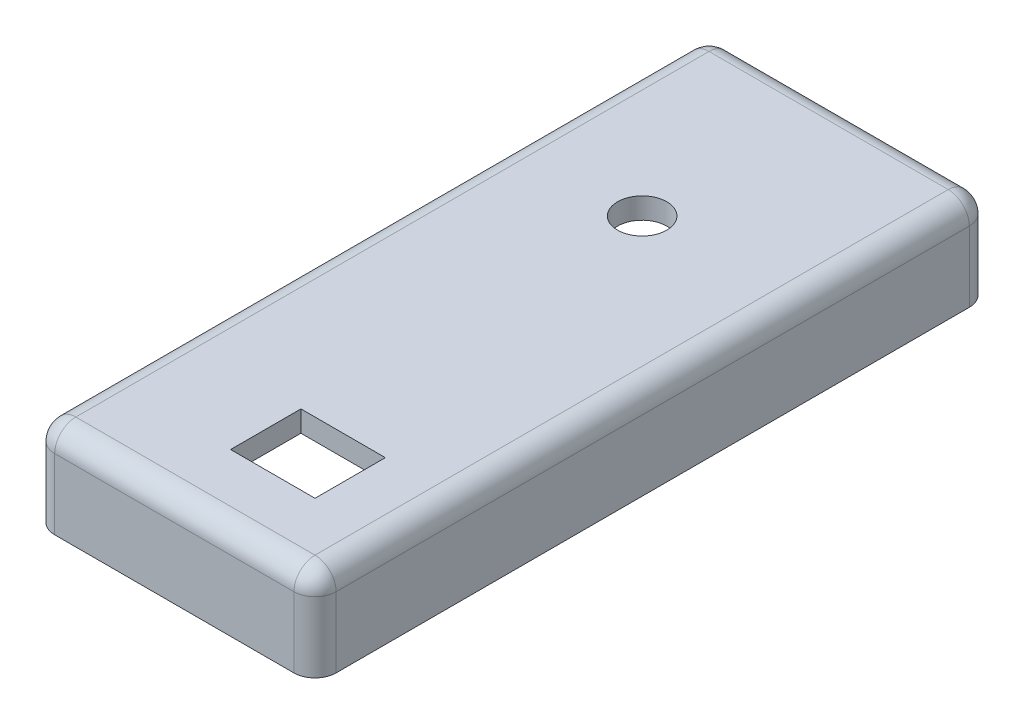
SolidWorks part; units mm, degrees
ref_plane "Plano frontal" through (0, 0, 0) normal (0, 0, 1) x (1, 0, 0)
ref_plane "Plano superior" through (0, 0, 0) normal (0, 1, 0) x (1, 0, 0)
ref_plane "Plano direito" through (0, 0, 0) normal (1, 0, 0) x (0, 0, -1)
sketch "Esboço1" plane through (0, 0, 0) normal (0, 1, 0) x (1, 0, 0)
  line L1 (-18.5576, 45.0701) -> (15.9424, 45.0701)
  line L2 (-18.5576, 45.0701) -> (-18.5576, -45.4299)
  line L3 (-18.5576, -45.4299) -> (15.9424, -45.4299)
  line L4 (15.9424, 45.0701) -> (15.9424, -45.4299)
  line L5 (-21.5576, 48.0701) -> (18.4424, 48.0701)
  line L6 (-21.5576, 48.0701) -> (-21.5576, -47.9299)
  line L7 (-21.5576, -47.9299) -> (18.4424, -47.9299)
  line L8 (18.4424, 48.0701) -> (18.4424, -47.9299)
extrude "Ressalto-extrusão1" add sketch "Esboço1" along normal blind 10
sketch "Esboço2" plane through (0, 10, 0) normal (0, 1, 0) x (1, 0, 0)
  line L1 (-21.5576, -47.9299) -> (18.4424, -47.9299)
  line L2 (-21.5576, -47.9299) -> (-21.5576, 48.0701)
  line L3 (-21.5576, 48.0701) -> (18.4424, 48.0701)
  line L4 (18.4424, -47.9299) -> (18.4424, 48.0701)
extrude "Ressalto-extrusão2" add sketch "Esboço2" along normal blind 3
sketch "Esboço3" plane through (0, 10, 0) normal (0, -1, 0) x (1, 0, 0)
  circle A0 centre (-4.5576, 23.4299) radius 3.5
extrude "Corte-extrusão1" cut sketch "Esboço3" against normal blind 3
sketch "Esboço4" plane through (0, 10, 0) normal (0, -1, 0) x (1, 0, 0)
  line L4 (-13.5576, -41.0701) -> (-1.5576, -41.0701)
  line L5 (-13.5576, -41.0701) -> (-13.5576, -31.0701)
  line L6 (-13.5576, -31.0701) -> (-1.5576, -31.0701)
  line L7 (-1.5576, -41.0701) -> (-1.5576, -31.0701)
extrude "Corte-extrusão2" cut sketch "Esboço4" against normal blind 3
fillet "Filete1" radius 3 8 edges at (-21.5576, 6.5, -48.0701) (18.4424, 6.5, -48.0701) (18.4424, 6.5, 47.9299) (-21.5576, 6.5, 47.9299) (-1.5576, 13, 47.9299) (18.4424, 13, -0.0701) (-1.5576, 13, -48.0701) (-21.5576, 13, -0.0701)
sketch "Esboço5" plane through (0, 10, 0) normal (0, -1, 0) x (1, 0, 0)
  line L1 (-1.5576, -31.0701) -> (-13.5576, -31.0701)
  line L2 (-1.5576, -31.0701) -> (-1.5576, -41.0701)
  line L3 (-1.5576, -41.0701) -> (-13.5576, -41.0701)
  line L4 (-13.5576, -31.0701) -> (-13.5576, -41.0701)
  circle A0 centre (-4.5576, 23.4299) radius 3.5 construction
  ellipse E0 centre (-4.5576, 23.4299) end of major axis (-4.5576, 19.9299) minor radius 3.5
extrude "Ressalto-extrusão3" add sketch "Esboço5" against normal blind 3
sketch "Esboço6" plane through (0, 10, 0) normal (0, -1, 0) x (1, 0, 0)
  circle A0 centre (-2.5576, 20.9299) radius 3.5
extrude "Corte-extrusão3" cut sketch "Esboço6" against normal blind 3
sketch "Esboço7" plane through (0, 10, 0) normal (0, -1, 0) x (1, 0, 0)
  line L0 (-18.5576, -45.0701) -> (-18.5576, -41.0701)
  line L1 (-18.5576, -45.0701) -> (-18.5576, 45.4299) construction
  line L2 (-18.5576, -41.0701) -> (-13.5576, -41.0701)
  line L4 (-13.5576, -41.0701) -> (-1.5576, -41.0701)
  line L5 (-13.5576, -41.0701) -> (-13.5576, -31.0701)
  line L6 (-13.5576, -31.0701) -> (-1.5576, -31.0701)
  line L7 (-1.5576, -41.0701) -> (-1.5576, -31.0701)
  dimension "D1" = 12
  dimension "D2" = 10
extrude "Corte-extrusão4" cut sketch "Esboço7" against normal blind 3 contours L4 L7 L6 L5
sketch "Esboço8" plane through (0, 10, 0) normal (0, -1, 0) x (1, 0, 0)
  line L1 (-1.5576, -31.0701) -> (-13.5576, -31.0701)
  line L2 (-1.5576, -31.0701) -> (-1.5576, -41.0701)
  line L3 (-1.5576, -41.0701) -> (-13.5576, -41.0701)
  line L4 (-13.5576, -31.0701) -> (-13.5576, -41.0701)
  circle A0 centre (-2.5576, 20.9299) radius 3.5
extrude "Ressalto-extrusão4" add sketch "Esboço8" against normal blind 3
sketch "Esboço9" plane through (0, 10, 0) normal (0, -1, 0) x (-1, 0, 0)
  line L5 (-8.4424, -37.9299) -> (3.5576, -37.9299)
  line L6 (-8.4424, -37.9299) -> (-8.4424, -27.9299)
  line L7 (-8.4424, -27.9299) -> (3.5576, -27.9299)
  line L8 (3.5576, -37.9299) -> (3.5576, -27.9299)
  circle A0 centre (3.0576, 20.0701) radius 3.5
extrude "Corte-extrusão5" cut sketch "Esboço9" against normal blind 3
